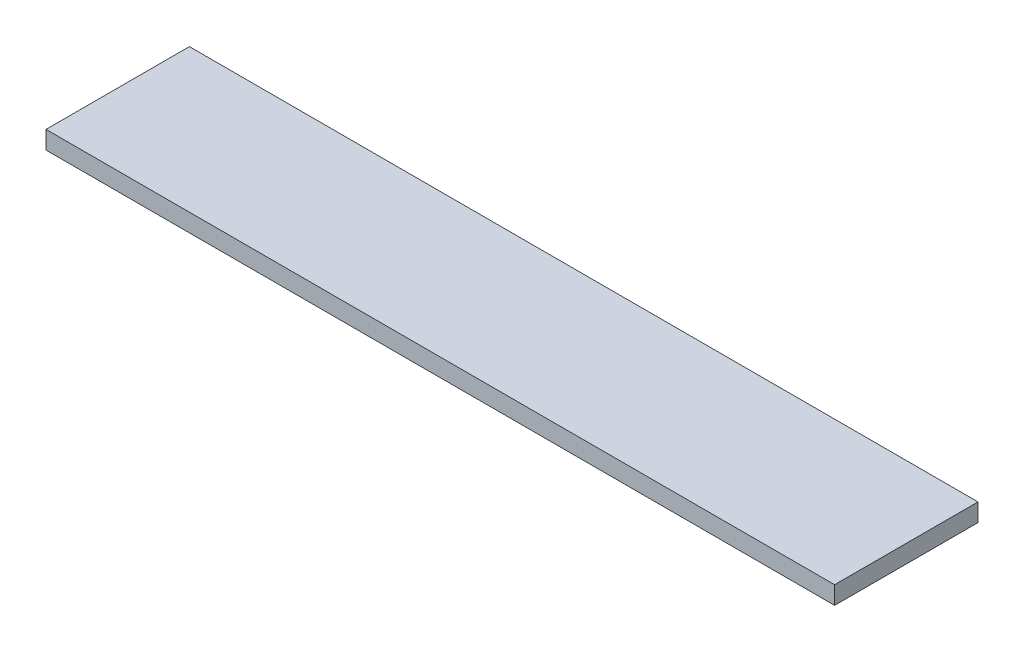
SolidWorks part; units mm, degrees
ref_plane "Front Plane" through (0, 0, 0) normal (0, 0, 1) x (1, 0, 0)
ref_plane "Top Plane" through (0, 0, 0) normal (0, 1, 0) x (1, 0, 0)
ref_plane "Right Plane" through (0, 0, 0) normal (1, 0, 0) x (0, 0, -1)
other "Configuration Table"
sketch "Sketch1" plane through (0, 0, 0) normal (0, 0, 1) x (1, 0, 0)
  line L1 (130, 460) -> (570, 460)
  line L2 (130, 460) -> (130, 470)
  line L3 (130, 470) -> (570, 470)
  line L4 (570, 460) -> (570, 470)
extrude "OVEN_kesme_kizak_plakasi_1" add sketch "Sketch1" against normal blind 80 from offset 260 separate body
